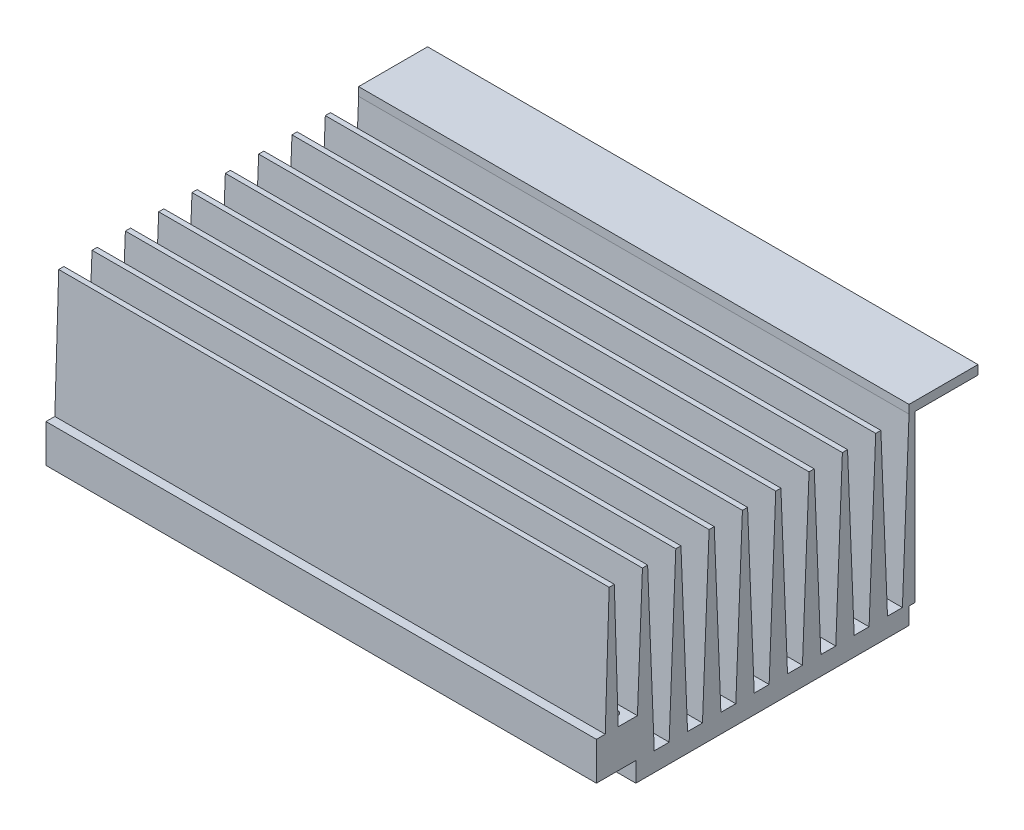
SolidWorks part; units mm, degrees
ref_plane "Front Plane" through (0, 0, 0) normal (0, 0, 1) x (1, 0, 0)
ref_plane "Top Plane" through (0, 0, 0) normal (0, 1, 0) x (1, 0, 0)
ref_plane "Right Plane" through (0, 0, 0) normal (1, 0, 0) x (0, 0, -1)
sketch "Sketch1" plane through (0, 0, 0) normal (0, 1, 0) x (1, 0, 0)
  line L1 (0, 0) -> (195.4375, 0)
  line L2 (0, 0) -> (0, 97)
  line L3 (0, 97) -> (195.4375, 97)
  line L4 (195.4375, 0) -> (195.4375, 97)
  dimension "D1" = 97
  dimension "D2" = 195.4375
extrude "Boss-Extrude1" add sketch "Sketch1" along normal blind 65
sketch "Sketch2" plane through (0, 0, 0) normal (-1, 0, 0) x (0, 0, 1)
  line L0 (-97, 65) -> (-94.65, 6.7)
  line L2 (-94.65, 6.7) -> (-89.35, 6.7)
  line L3 (-89.35, 6.7) -> (-87, 65)
  line L4 (-97, 65) -> (0, 65) construction
  line L5 (-87, 65) -> (-97, 65)
  line L7 (-97, 0) -> (0, 0) construction
  line L8 (-92, 6.7) -> (-92, 65) construction
  line L37 (-75.1687, 65) -> (-85.1687, 65)
  line L38 (-85.1687, 65) -> (-82.8187, 6.7)
  line L39 (-82.8187, 6.7) -> (-77.5187, 6.7)
  line L40 (-77.5187, 6.7) -> (-75.1687, 65)
  line L41 (-63.3375, 65) -> (-73.3375, 65)
  line L42 (-73.3375, 65) -> (-70.9875, 6.7)
  line L43 (-70.9875, 6.7) -> (-65.6875, 6.7)
  line L44 (-65.6875, 6.7) -> (-63.3375, 65)
  line L45 (-51.5062, 65) -> (-61.5062, 65)
  line L46 (-61.5062, 65) -> (-59.1562, 6.7)
  line L47 (-59.1562, 6.7) -> (-53.8563, 6.7)
  line L48 (-53.8563, 6.7) -> (-51.5062, 65)
  line L49 (-39.675, 65) -> (-49.675, 65)
  line L50 (-49.675, 65) -> (-47.325, 6.7)
  line L51 (-47.325, 6.7) -> (-42.025, 6.7)
  line L52 (-42.025, 6.7) -> (-39.675, 65)
  line L53 (-27.8437, 65) -> (-37.8437, 65)
  line L54 (-37.8437, 65) -> (-35.4937, 6.7)
  line L55 (-35.4937, 6.7) -> (-30.1937, 6.7)
  line L56 (-30.1937, 6.7) -> (-27.8437, 65)
  line L57 (-16.0125, 65) -> (-26.0125, 65)
  line L58 (-26.0125, 65) -> (-23.6625, 6.7)
  line L59 (-23.6625, 6.7) -> (-18.3625, 6.7)
  line L60 (-18.3625, 6.7) -> (-16.0125, 65)
  line L61 (-4.1812, 65) -> (-14.1812, 65)
  line L62 (-14.1812, 65) -> (-11.8313, 6.7)
  line L63 (-11.8313, 6.7) -> (-6.5313, 6.7)
  line L64 (-6.5313, 6.7) -> (-4.1812, 65)
  line L65 (7.65, 65) -> (-2.35, 65)
  line L66 (-2.35, 65) -> (0, 6.7)
  line L67 (0, 6.7) -> (5.3, 6.7)
  line L68 (5.3, 6.7) -> (7.65, 65)
  line L69 (0, 65) -> (0, 0) construction
  dimension "D1" = 10
  dimension "D2" = 5.3
  dimension "D3" = 6.7
  dimension "D4" = 9
extrude "Cut-Extrude1" cut sketch "Sketch2" against normal through all
ref_plane "Plane1" through (0, 7, 0) normal (0, -1, 0) x (-1, 0, 0)
sketch "Sketch4" plane through (0, 7, 0) normal (0, -1, 0) x (-1, 0, 0)
  line L0 (-195.4375, 0) -> (-195.4375, 97) construction
  line L1 (0, 1) -> (-195.4375, 1)
  line L2 (0, 1) -> (0, -14)
  line L3 (0, -14) -> (-195.4375, -14)
  line L4 (-195.4375, 1) -> (-195.4375, -14)
  line L5 (0, 97) -> (0, 0) construction
  dimension "D1" = 1
  dimension "D2" = 15
extrude "Boss-Extrude2" add sketch "Sketch4" against normal blind 13.5
sketch "Sketch5" plane through (0, 0, 0) normal (-1, 0, 0) x (0, 0, 1)
  line L0 (6.2656, 20.5) -> (7.65, 65)
  line L1 (14, 20.5) -> (-0.5563, 20.5) construction
  line L2 (7.65, 65) -> (9.4813, 65)
  line L3 (9.4813, 65) -> (10.8656, 20.5)
  line L4 (-14.1812, 65) -> (-4.1812, 65) construction
  line L5 (-2.35, 65) -> (7.65, 65) construction
  line L6 (-4.1812, 65) -> (-2.35, 65) construction
  line L7 (6.2656, 20.5) -> (10.8656, 20.5)
  line L8 (8.5656, 65) -> (8.5656, 20.5) construction
  line L10 (-21.0125, 6.7) -> (-9.1813, 6.7) construction
  line L11 (-23.6625, 6.7) -> (-18.3625, 6.7) construction
  line L12 (-11.8313, 6.7) -> (-6.5313, 6.7) construction
  dimension "D1" = 4.6
extrude "Boss-Extrude3" add sketch "Sketch5" against normal up to surface (195.4375 mm away) up to face at (195.4375, 31.8475, -42.2705)
ref_plane "Plane2" through (0, 6, 0) normal (0, -1, 0) x (-1, 0, 0)
sketch "Sketch6" plane through (0, 6, 0) normal (0, -1, 0) x (-1, 0, 0)
  line L0 (-195.4375, 0) -> (-195.4375, 97) construction
  line L1 (0, 97) -> (-195.4375, 97)
  line L2 (0, 97) -> (0, 99.19)
  line L3 (0, 99.19) -> (-195.4375, 99.19)
  line L4 (-195.4375, 97) -> (-195.4375, 99.19)
  line L5 (0, 97) -> (0, 0) construction
  line L6 (-195.4375, 97) -> (0, 97) construction
  dimension "D1" = 2.19
extrude "Boss-Extrude4" add sketch "Sketch6" against normal blind 62
sketch "Sketch7" plane through (0, 0, -99.19) normal (0, 0, -1) x (-1, 0, 0)
  line L0 (0, 68) -> (0, 6) construction
  line L1 (-195.4375, 68) -> (0, 68)
  line L2 (-195.4375, 68) -> (-195.4375, 64.76)
  line L3 (-195.4375, 64.76) -> (0, 64.76)
  line L4 (0, 68) -> (0, 64.76)
  dimension "D1" = 3.24
extrude "Boss-Extrude5" add sketch "Sketch7" along normal blind 22.3
sketch "Sketch8" plane through (0, 6.7, 0) normal (0, 1, 0) x (1, 0, 0)
  line L0 (195.4375, -14) -> (0, -14) construction
  line L1 (195.4375, -14) -> (0, -14)
  line L2 (97.7188, -14) -> (97.7188, 115.2245) construction
  line L3 (195.4375, 0.5563) -> (195.4375, -6.2656) construction
  line L4 (195.4375, 0.5563) -> (195.4375, -6.2656)
  line L5 (195.4375, 94.65) -> (195.4375, 89.35) construction
  line L6 (195.4375, 94.65) -> (195.4375, 89.35)
  circle A0 centre (190.4375, 92) radius 1.5
  circle A1 centre (190.4375, -2.8547) radius 1.5
  circle A2 centre (5, 92) radius 1.5
  circle A3 centre (5, -2.8547) radius 1.5
  point P8 (97.7188, -14)
  point P12 (195.4375, -2.8547)
  point P15 (195.4375, 92)
  dimension "D2" = 3
  dimension "D1" = 5
extrude "Cut-Extrude2" cut sketch "Sketch8" against normal through all and the other way through all contours A2 | A0 | A3 | A1
